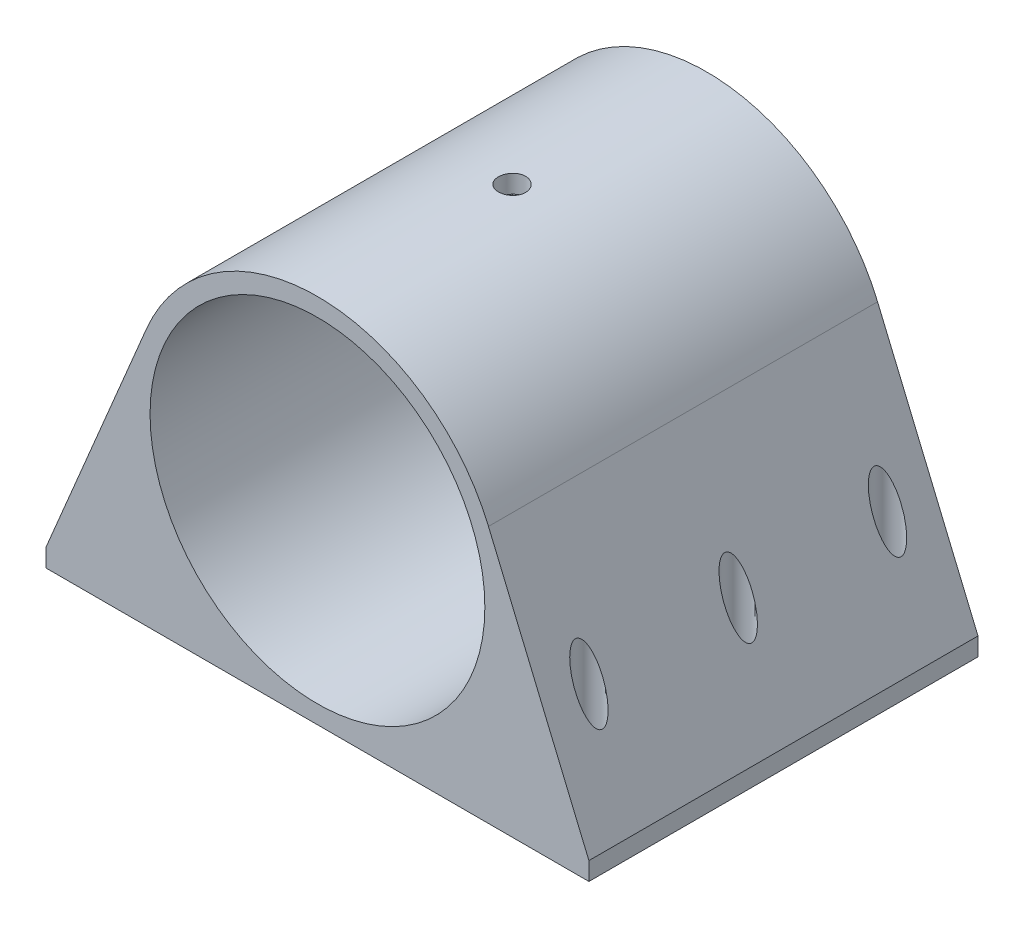
SolidWorks part; units mm, degrees
ref_plane "Спереди" through (0, 0, 0) normal (0, 0, 1) x (1, 0, 0)
ref_plane "Сверху" through (0, 0, 0) normal (0, 1, 0) x (1, 0, 0)
ref_plane "Справа" through (0, 0, 0) normal (1, 0, 0) x (0, 0, -1)
sketch "Эскиз1" plane through (0, 0, 0) normal (0, 0, 1) x (1, 0, 0)
  line L0 (0, -20.5) -> (-30, -20.5)
  line L1 (0, -20.5) -> (30, -20.5)
  line L3 (-30, -18.5) -> (-30, -20.5)
  line L5 (30, -18.5) -> (30, -20.5)
  line L6 (-30, -18.5) -> (-18.9018, 7.9354)
  line L7 (30, -18.5) -> (18.9018, 7.9354)
  circle A0 centre (0, 0) radius 18.5
  arc A1 (18.9018, 7.9354) -> (-18.9018, 7.9354) centre (0, 0) ccw
  circle A2 centre (0, 7) radius 6.35
  circle A3 centre (15.5, 0) radius 2.1
  circle A4 centre (7.75, -13.4234) radius 2.1
  circle A5 centre (-7.75, -13.4234) radius 2.1
  circle A6 centre (-15.5, 0) radius 2.1
  circle A7 centre (-7.75, 13.4234) radius 2.1
  circle A8 centre (7.75, 13.4234) radius 2.1
  point P28 (0, 0)
  dimension "D1" = 37
  dimension "D2" = 41
  dimension "D6" = 12.7
  dimension "D7" = 4.2
  dimension "D3" = 30
  dimension "D4" = 30
  dimension "D5" = 7
  dimension "D8" = 15.5
  dimension "D9" = 6
extrude "Бобышка-Вытянуть1" add sketch "Эскиз1" along normal blind 43 contours L7 A1 L6 L3 L0 L1 L5 A0 | A0 A8 A7 A6 A5 A4 A3 A2
sketch "Эскиз2" plane through (0, 0, 43) normal (0, 0, 1) x (1, 0, 0)
  circle A0 centre (0, 0) radius 18.5
  dimension "D1" = 37
extrude "Вырез-Вытянуть1" cut sketch "Эскиз2" against normal blind 40
sketch "Эскиз3" plane through (0, -20.5, 0) normal (0, -1, 0) x (-1, 0, 0)
  line L0 (30, -43) -> (30, 0) construction
  line L1 (-30, -43) -> (30, -43) construction
  line L2 (-30, 0) -> (30, 0) construction
  line L3 (-30, -43) -> (-30, 0) construction
  circle A0 centre (25, -38) radius 1.5
  circle A1 centre (25, -21.5) radius 1.5
  circle A2 centre (25, -5) radius 1.5
  circle A3 centre (-25, -38) radius 1.5
  circle A4 centre (-25, -21.5) radius 1.5
  circle A5 centre (-25, -5) radius 1.5
  point P18 (0, 0)
  point P21 (0, 0)
  point P23 (-24.7101, -43.6396)
  dimension "D1" = 3
  dimension "D2" = 3
  dimension "D3" = 3
  dimension "D4" = 3
  dimension "D5" = 3
  dimension "D6" = 3
  dimension "D7" = 5
  dimension "D8" = 5
  dimension "D9" = 5
  dimension "D10" = 21.5
  dimension "D11" = 5
  dimension "D12" = 5
  dimension "D13" = 5
  dimension "D14" = 5
  dimension "D15" = 5
  dimension "D16" = 21.5
  dimension "D17" = 5
  dimension "D18" = 5
extrude "Вырез-Вытянуть2" cut sketch "Эскиз3" against normal blind 40
sketch "Эскиз4" plane through (0, -20.5, 0) normal (0, -1, 0) x (-1, 0, 0)
  line L0 (-30, 0) -> (30, 0) construction
  line L1 (-30, -43) -> (-30, 0) construction
  circle A0 centre (0, -21.5) radius 1.5
  dimension "D1" = 3
  dimension "D2" = 21.5
  dimension "D3" = 30
extrude "Вырез-Вытянуть3" cut sketch "Эскиз4" against normal blind 100
